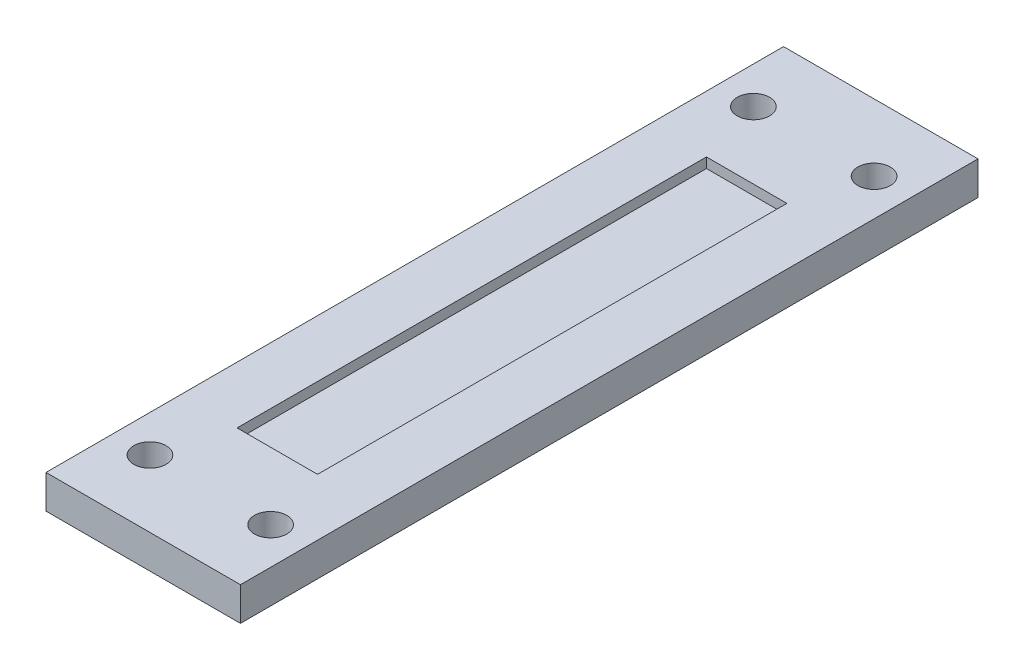
SolidWorks part; units mm, degrees
ref_plane "Front Plane" through (0, 0, 0) normal (0, 0, 1) x (1, 0, 0)
ref_plane "Top Plane" through (0, 0, 0) normal (0, 1, 0) x (1, 0, 0)
ref_plane "Right Plane" through (0, 0, 0) normal (1, 0, 0) x (0, 0, -1)
sketch "Sketch1" plane through (0, 0, 0) normal (0, 1, 0) x (1, 0, 0)
  line L1 (-14.5, 55) -> (14.5, 55)
  line L2 (-14.5, 55) -> (-14.5, -55)
  line L3 (-14.5, -55) -> (14.5, -55)
  line L4 (14.5, 55) -> (14.5, -55)
  dimension "D1" = 29
  dimension "D2" = 110
  dimension "D3" = 55
  dimension "D4" = 14.5
extrude "Boss-Extrude1" add sketch "Sketch1" along normal blind 5
sketch "Sketch2" plane through (0, 5, 0) normal (0, 1, 0) x (1, 0, 0)
  line L0 (-14.5, 55) -> (-14.5, -55) construction
  line L1 (14.5, -55) -> (14.5, 55) construction
  line L2 (14.5, 55) -> (-14.5, 55) construction
  line L3 (-14.5, -55) -> (14.5, -55) construction
  circle A0 centre (-9, 45) radius 2.413
  circle A1 centre (9, 45) radius 2.413
  circle A2 centre (9, -45) radius 2.413
  circle A3 centre (-9, -45) radius 2.413
  dimension "D1" = 4.826
  dimension "D2" = 5.5
  dimension "D3" = 5.5
  dimension "D4" = 10
  dimension "D5" = 10
extrude "Cut-Extrude5" cut sketch "Sketch2" against normal through all
sketch "Sketch3" plane through (0, 5, 0) normal (0, 1, 0) x (1, 0, 0)
  line L1 (-6, 35) -> (6, 35)
  line L2 (-6, 35) -> (-6, -35)
  line L3 (-6, -35) -> (6, -35)
  line L4 (6, 35) -> (6, -35)
  dimension "D1" = 12
  dimension "D2" = 70
  dimension "D3" = 35
  dimension "D4" = 6
extrude "Cut-Extrude6" cut sketch "Sketch3" against normal blind 1.5
